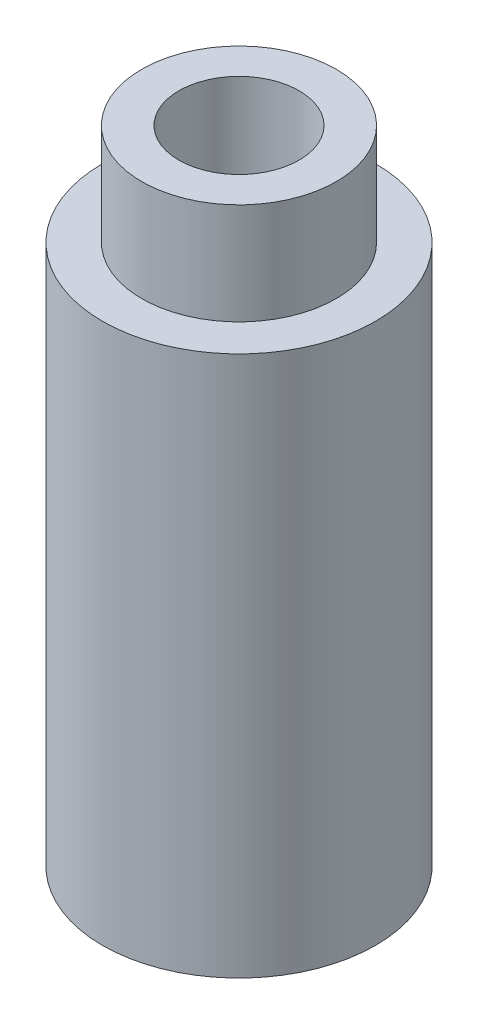
SolidWorks part; units mm, degrees
ref_plane "Front Plane" through (0, 0, 0) normal (0, 0, 1) x (1, 0, 0)
ref_plane "Top Plane" through (0, 0, 0) normal (0, 1, 0) x (1, 0, 0)
ref_plane "Right Plane" through (0, 0, 0) normal (1, 0, 0) x (0, 0, -1)
sketch "Sketch1" plane through (0, 0, 0) normal (0, 1, 0) x (1, 0, 0)
  circle A0 centre (0, 0) radius 12.827
  dimension "D1" = 25.654
extrude "Boss-Extrude1" add sketch "Sketch1" along normal blind 50.8
sketch "Sketch2" plane through (0, 50.8, 0) normal (0, 1, 0) x (1, 0, 0)
  circle A0 centre (0, 0) radius 9.144
  dimension "D1" = 18.288
extrude "Boss-Extrude2" add sketch "Sketch2" along normal blind 9.525
sketch "Sketch3" plane through (0, 60.325, 0) normal (0, 1, 0) x (1, 0, 0)
  circle A0 centre (0, 0) radius 5.6515
  point P2 (0, 0)
  dimension "D1" = 11.303
extrude "Cut-Extrude1" cut sketch "Sketch3" against normal blind 59.69
